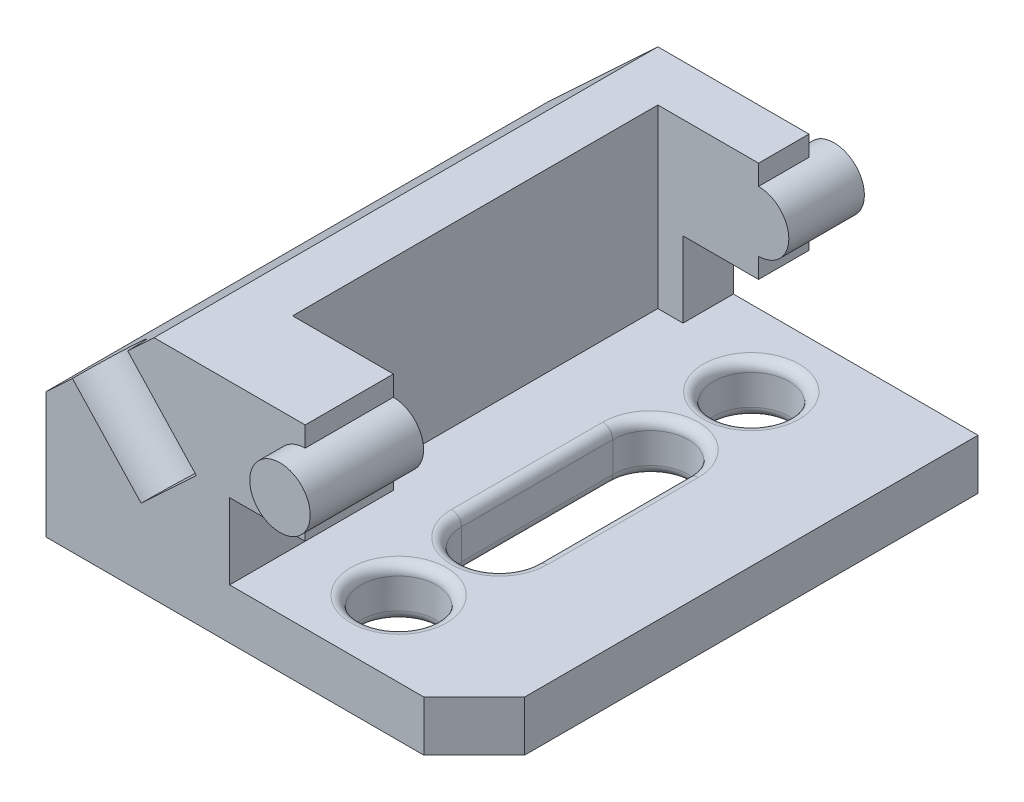
SolidWorks part; units mm, degrees
material "Alliage 1060"
ref_plane "Plan de face" through (0, 0, 0) normal (0, 0, 1) x (1, 0, 0)
ref_plane "Plan de dessus" through (0, 0, 0) normal (0, 1, 0) x (1, 0, 0)
ref_plane "Plan de droite" through (0, 0, 0) normal (1, 0, 0) x (0, 0, -1)
sketch "Esquisse1" plane through (0, 0, 0) normal (0, 0, 1) x (1, 0, 0)
  line L19 (0, 0) -> (0, 25)
  line L20 (0, 25) -> (21.4474, 45)
  line L21 (21.4474, 45) -> (51.4474, 45)
  line L22 (51.4474, 45) -> (51.4474, 25)
  line L23 (51.4474, 25) -> (36.4474, 25)
  line L24 (36.4474, 25) -> (36.4474, 10)
  line L25 (36.4474, 10) -> (85, 10)
  line L26 (85, 10) -> (85, 0)
  line L27 (85, 0) -> (0, 0)
  dimension "D1" = 85
  dimension "D2" = 30
  dimension "D3" = 20
  dimension "D4" = 15
  dimension "D5" = 15
  dimension "D6" = 10
  dimension "D7" = 25
  dimension "D8" = 47
extrude "Boss.-Extru.1" add sketch "Esquisse1" along normal mid plane 100
sketch "Esquisse3" plane through (0, 0, 0) normal (0, 0, 1) x (1, 0, 0)
  line L0 (51.4474, 25) -> (51.4474, 45) construction
  line L1 (51.4474, 45) -> (21.4474, 45) construction
  circle A0 centre (51.4474, 35) radius 6
  dimension "D1" = 12
  dimension "D2" = 10
extrude "Boss.-Extru.2" add sketch "Esquisse3" along normal blind 55 and the other way blind 55
sketch "Esquisse4" plane through (0, 45, 0) normal (0, 1, 0) x (1, 0, 0)
  line L0 (57.4474, -55) -> (57.4474, 55) construction
  line L1 (57.4474, 40) -> (31.4474, 40)
  line L2 (57.4474, 40) -> (57.4474, -32.5)
  line L3 (57.4474, -32.5) -> (31.4474, -32.5)
  line L4 (31.4474, 40) -> (31.4474, -32.5)
  line L5 (21.4474, -50) -> (21.4474, 50) construction
  line L6 (51.4474, 50) -> (21.4474, 50) construction
  dimension "D1" = 10
  dimension "D2" = 10
  dimension "D3" = 72.5
extrude "Enlèv. mat.-Extru.1" cut sketch "Esquisse4" against normal blind 35
sketch "Esquisse5" plane through (-12.4696, 13.372, 0) normal (-0.682, 0.7314, 0) x (0.7314, 0.682, 0)
  line L0 (46.3755, -50) -> (17.05, -50) construction
  circle A0 centre (31.7128, -50) radius 7.5
  dimension "D1" = 15
extrude "Enlèv. mat.-Extru.2" cut sketch "Esquisse5" against normal blind 20
sketch "Esquisse8" plane through (0, 10, 0) normal (0, 1, 0) x (1, 0, 0)
  line L0 (85, -50) -> (85, 50) construction
  line L2 (85, -50) -> (36.4474, -50) construction
  line L3 (85, 50) -> (36.4474, 50) construction
  line L4 (55, 15) -> (55, -15) construction
  line L5 (62.5, 15) -> (62.5, -15)
  line L6 (47.5, 15) -> (47.5, -15)
  circle A1 centre (55, -35) radius 7.5
  circle A2 centre (55, 35) radius 7.5
  arc A3 (62.5, 15) -> (47.5, 15) centre (55, 15) ccw
  arc A4 (47.5, -15) -> (62.5, -15) centre (55, -15) ccw
  point P12 (55, 0)
  dimension "D1" = 15
  dimension "D2" = 15
  dimension "D7" = 15
  dimension "D3" = 30
  dimension "D4" = 30
  dimension "D5" = 15
  dimension "D6" = 15
  dimension "D8" = 30
  dimension "D9" = 20
extrude "Enlèv. mat.-Extru.3" cut sketch "Esquisse8" against normal through all
fillet "Congé1" radius 2 8 edges at (55, 0, -22.5) (62.5, 0, 0) (55, 0, 22.5) (55, 10, -22.5) (62.5, 10, 0) (55, 10, 22.5) (47.5, 0, 0) (47.5, 10, 0)
fillet "Congé2" radius 2 4 edges at (47.5, 10, 35) (47.5, 0, 35) (47.5, 10, -35) (47.5, 0, -35)
chamfer "Chanfrein3" distance 10 angle 45 1 edges at (85, 5, 50)
equation "\"A\" = 85mm"
equation "\"B\" = 72.50mm"
equation "\"C\"= 47"
equation "\"D1@Esquisse1\"=\"A\""
equation "\"D8@Esquisse1\"=\"C\""
equation "\"D3@Esquisse4\"=\"B\""
